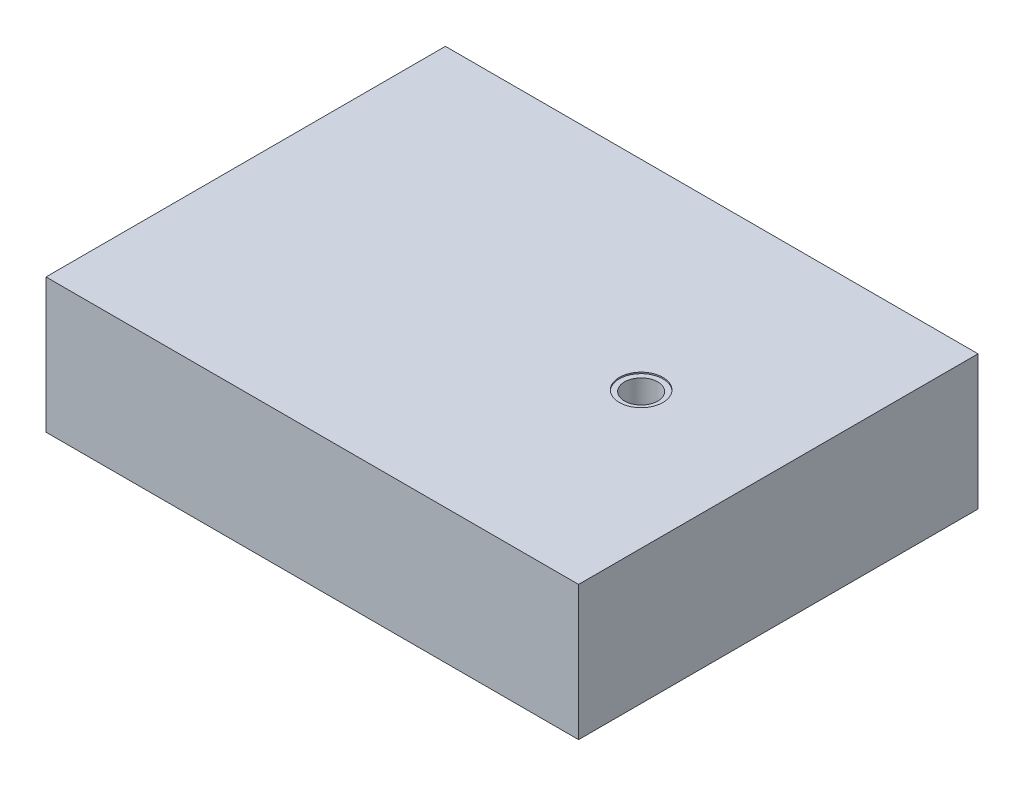
SolidWorks part; units mm, degrees
ref_plane "Front Plane" through (0, 0, 0) normal (0, 0, 1) x (1, 0, 0)
ref_plane "Top Plane" through (0, 0, 0) normal (0, 1, 0) x (1, 0, 0)
ref_plane "Right Plane" through (0, 0, 0) normal (1, 0, 0) x (0, 0, -1)
sketch "Sketch1" plane through (0, 0, 0) normal (0, 1, 0) x (1, 0, 0)
  line L1 (0, 0) -> (4, 0)
  line L2 (0, 0) -> (0, 3)
  line L3 (0, 3) -> (4, 3)
  line L4 (4, 0) -> (4, 3)
  dimension "D1" = 4
  dimension "D2" = 3
extrude "Boss-Extrude1" add sketch "Sketch1" along normal blind 1
sketch "Sketch2" plane through (0, 1, 0) normal (0, 1, 0) x (1, 0, 0)
  line L0 (4, 3) -> (0, 3) construction
  line L1 (4, 0) -> (4, 3) construction
  circle A0 centre (2.97, 1.5) radius 0.125
  dimension "D3" = 0.25
  dimension "D1" = 1.5
  dimension "D2" = 1.03
extrude "Cut-Extrude1" cut sketch "Sketch2" against normal blind 0.2
sketch "Sketch3" plane through (0, 1, 0) normal (0, 1, 0) x (1, 0, 0)
  line L1 (0, 3) -> (4, 3)
  line L2 (0, 3) -> (0, 0)
  line L3 (0, 0) -> (4, 0)
  line L4 (4, 3) -> (4, 0)
  circle A0 centre (2.97, 1.5) radius 0.1637
extrude "Boss-Extrude2" add sketch "Sketch3" along normal blind 0.01
